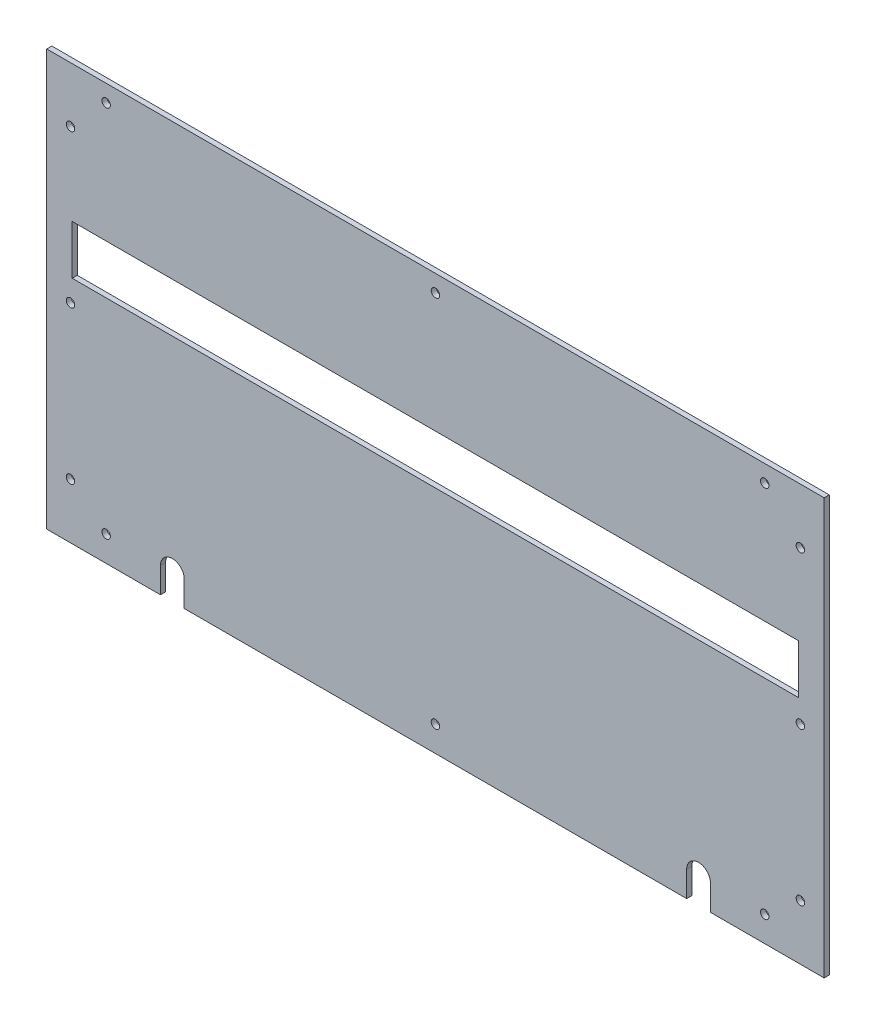
SolidWorks part; units mm, degrees
material "1345 Alloy"
ref_plane "Front Plane" through (0, 0, 0) normal (0, 0, 1) x (1, 0, 0)
ref_plane "Top Plane" through (0, 0, 0) normal (0, 1, 0) x (1, 0, 0)
ref_plane "Right Plane" through (0, 0, 0) normal (1, 0, 0) x (0, 0, -1)
sketch "Sketch1" plane through (0, 0, 0) normal (0, 0, 1) x (1, 0, 0)
  line L1 (-229, 122.5) -> (229, 122.5)
  line L2 (-229, 122.5) -> (-229, -122.5)
  line L3 (-229, -122.5) -> (229, -122.5)
  line L4 (229, 122.5) -> (229, -122.5)
  line L5 (-229, 122.5) -> (229, -122.5) construction
  line L6 (-229, -122.5) -> (229, 122.5) construction
  point P0 (0, 0)
  dimension "D1" = 458
  dimension "D2" = 245
extrude "Boss-Extrude1" add sketch "Sketch1" along normal blind 3
sketch "Sketch2" plane through (0, 0, 3) normal (0, 0, 1) x (1, 0, 0)
  line L0 (-229, -122.5) -> (-155, -122.5) construction
  line L1 (-229, -122.5) -> (229, -122.5) construction
  line L2 (-155, -122.5) -> (-155, -107.5) construction
  line L3 (-155, -107.5) -> (-155, -122.5) construction
  line L4 (-148, -107.5) -> (-148, -122.5)
  line L5 (-162, -107.5) -> (-162, -122.5)
  line L6 (155, -122.5) -> (229, -122.5) construction
  line L8 (155, -107.5) -> (155, -122.5) construction
  line L9 (162, -107.5) -> (162, -122.5)
  line L10 (148, -107.5) -> (148, -122.5)
  line L11 (-155, -107.5) -> (155, -107.5) construction
  arc A0 (-148, -107.5) -> (-162, -107.5) centre (-155, -107.5) ccw
  arc A1 (-162, -122.5) -> (-148, -122.5) centre (-155, -122.5) ccw
  arc A2 (162, -107.5) -> (148, -107.5) centre (155, -107.5) ccw
  arc A3 (148, -122.5) -> (162, -122.5) centre (155, -122.5) ccw
  point P6 (-155, -115)
  point P15 (155, -115)
  dimension "D3" = 7
  dimension "D5" = 7
  dimension "D1" = 74
  dimension "D2" = 15
  dimension "D4" = 15
  dimension "D6" = 74
extrude "Cut-Extrude1" cut sketch "Sketch2" against normal through all
sketch "Sketch3" plane through (0, 0, 3) normal (0, 0, 1) x (1, 0, 0)
  line L1 (-229, 122.5) -> (-229, -122.5) construction
  line L2 (-229, 122.5) -> (-194, 122.5) construction
  line L3 (229, 122.5) -> (-229, 122.5) construction
  line L18 (194, 112.5) -> (194, -107.5) construction
  line L19 (-215, 0) -> (-215, 90) construction
  line L20 (-215, 0) -> (-215, -90) construction
  line L21 (229, 0) -> (215, 0) construction
  line L22 (0, 112.5) -> (-194, 112.5) construction
  line L23 (229, -122.5) -> (229, 122.5) construction
  line L24 (-194, 112.5) -> (-194, -107.5) construction
  line L25 (215, 0) -> (215, 90) construction
  line L26 (215, 0) -> (215, -90) construction
  line L27 (0, 112.5) -> (194, 112.5) construction
  line L28 (0, 0) -> (0, 112.5) construction
  line L29 (0, 0) -> (0, -107.5) construction
  line L30 (-194, -107.5) -> (0, -107.5) construction
  line L31 (162, -122.5) -> (229, -122.5) construction
  line L32 (-229, -122.5) -> (-162, -122.5) construction
  line L34 (0, -107.5) -> (194, -107.5) construction
  line L35 (-194, 112.5) -> (-229, 112.5) construction
  line L36 (-229, 112.5) -> (-229, 122.5) construction
  circle A0 centre (-194, 112.5) radius 2.5
  circle A1 centre (-194, -107.5) radius 2.5
  circle A2 centre (194, -107.5) radius 2.5
  circle A3 centre (194, 112.5) radius 2.5
  circle A4 centre (-215, 0) radius 2.5
  circle A5 centre (-215, -90) radius 2.5
  circle A6 centre (-215, 90) radius 2.5
  circle A7 centre (215, 0) radius 2.5
  circle A8 centre (215, -90) radius 2.5
  circle A9 centre (215, 90) radius 2.5
  circle A10 centre (0, 112.5) radius 2.5
  circle A11 centre (0, -107.5) radius 2.5
  dimension "D3" = 5
  dimension "D6" = 5
  dimension "D9" = 5
  dimension "D12" = 5
  dimension "D15" = 5
  dimension "D16" = 5
  dimension "D17" = 5
  dimension "D21" = 5
  dimension "D22" = 5
  dimension "D2" = 35
  dimension "D4" = 15
  dimension "D5" = 14
  dimension "D7" = 15
  dimension "D8" = 14
  dimension "D10" = 194
  dimension "D11" = 10
  dimension "D13" = 90
  dimension "D14" = 90
  dimension "D18" = 14
  dimension "D19" = 90
  dimension "D20" = 90
  dimension "D23" = 194
  dimension "D24" = 194
  dimension "D25" = 35
  dimension "D26" = 194
extrude "Cut-Extrude2" cut sketch "Sketch3" against normal through all
sketch "Sketch4" plane through (0, 0, 3) normal (0, 0, 1) x (1, 0, 0)
  line L0 (-229, -122.5) -> (-229, 27.5) construction
  line L1 (-229, 122.5) -> (-229, -122.5) construction
  line L2 (-229, 27.5) -> (229, 27.5) construction
  line L3 (229, -122.5) -> (229, 122.5) construction
  line L4 (-229, 27.5) -> (-229, 42) construction
  line L5 (-229, 42) -> (-214, 42) construction
  line L6 (229, 27.5) -> (229, 42) construction
  line L7 (229, 42) -> (214, 42) construction
  line L8 (214, 42) -> (-214, 42)
  line L9 (-214, 42) -> (-214, 13)
  line L10 (-214, 13) -> (214, 13)
  line L11 (214, 13) -> (214, 42)
  dimension "D1" = 150
  dimension "D2" = 14.5
  dimension "D3" = 15
  dimension "D4" = 14.5
  dimension "D5" = 15
  dimension "D6" = 29
extrude "Cut-Extrude3" cut sketch "Sketch4" against normal through all
